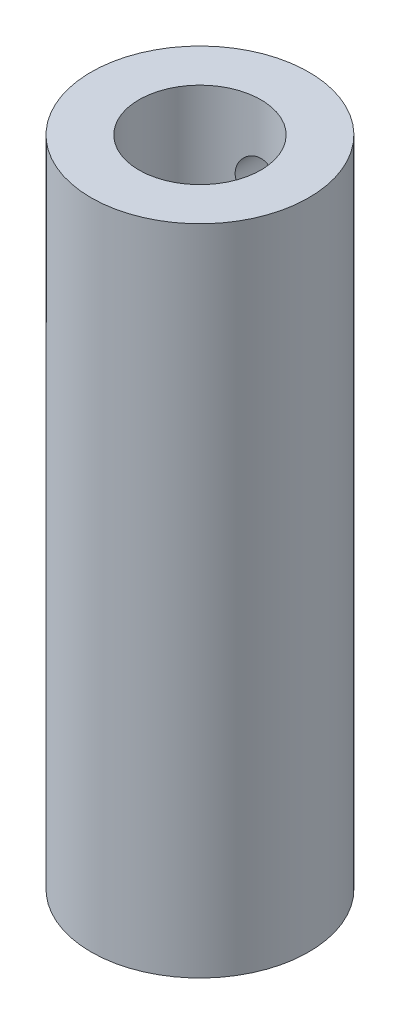
SolidWorks part; units mm, degrees
ref_plane "Ön Düzlem" through (0, 0, 0) normal (0, 0, 1) x (1, 0, 0)
ref_plane "Üst Düzlem" through (0, 0, 0) normal (0, 1, 0) x (1, 0, 0)
ref_plane "Sağ Düzlem" through (0, 0, 0) normal (1, 0, 0) x (0, 0, -1)
sketch "Çizim1" plane through (0, 0, 0) normal (0, 1, 0) x (1, 0, 0)
  line L0 (-1.65, 2.2) -> (1.65, 2.2)
  arc A0 (-1.65, 2.2) -> (1.65, 2.2) centre (0, 0) ccw
  circle A1 centre (0, 0) radius 7.5
  dimension "D1" = 5.5
  dimension "D3" = 15
  dimension "D2" = 2.2
extrude "Yükseklik-Ekstrüzyon1" add sketch "Çizim1" along normal blind 15
sketch "Çizim2" plane through (0, 15, 0) normal (0, 1, 0) x (1, 0, 0)
  circle A0 centre (0, 0) radius 4.2
  circle A1 centre (0, 0) radius 7.5
  circle A2 centre (0, 0) radius 7.5 construction
  dimension "D1" = 8.4
extrude "Yükseklik-Ekstrüzyon2" add sketch "Çizim2" along normal blind 30
sketch "Çizim3" plane through (0, 0, 0) normal (0, 0, 1) x (1, 0, 0)
  line L0 (4.2, 45) -> (-4.2, 45) construction
  circle A0 centre (0, 40) radius 1.5
  circle A1 centre (0, 35) radius 1.5
  circle A2 centre (0, 30) radius 1.5
  circle A3 centre (0, 10) radius 1.5
  circle A4 centre (0, 5) radius 1.5
  dimension "D1" = 3
  dimension "D2" = 5
  dimension "D3" = 5
  dimension "D4" = 5
  dimension "D5" = 5
  dimension "D6" = 5
extrude "Kes-Ekstrüzyon1" cut sketch "Çizim3" against normal blind 10
